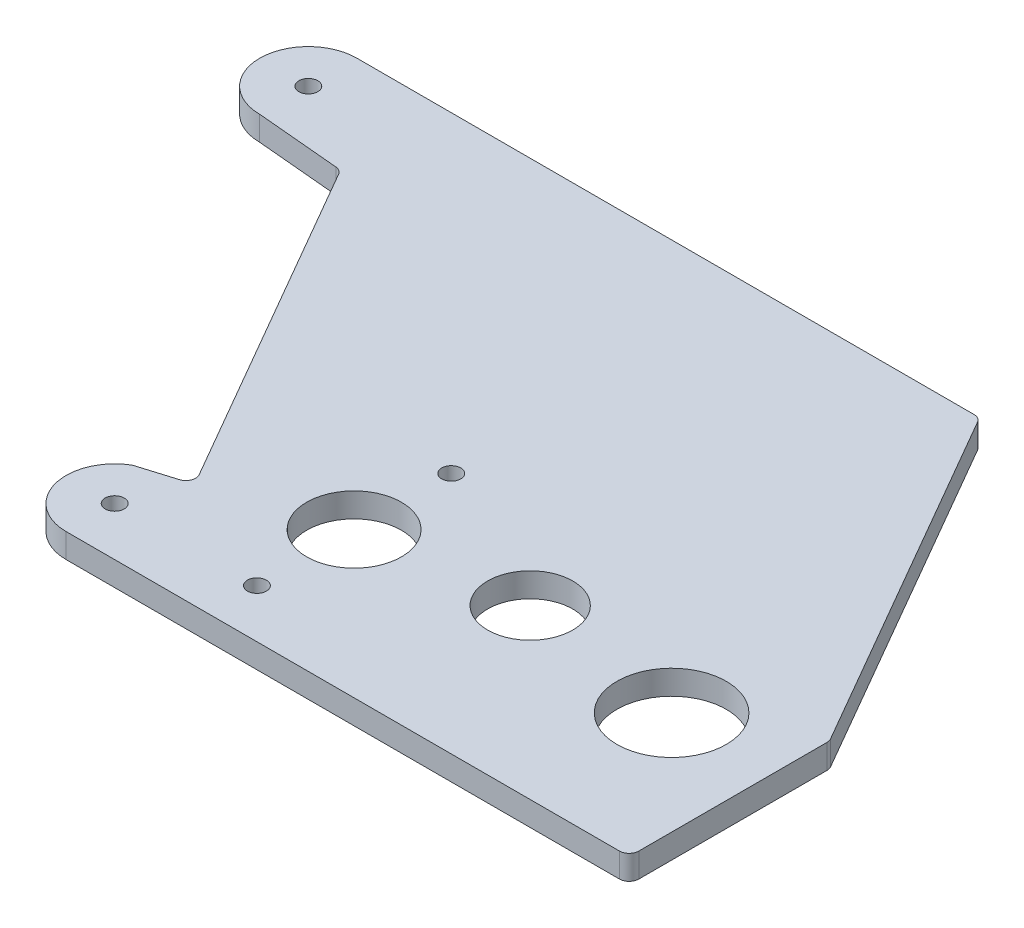
SolidWorks part; units mm, degrees
ref_plane "Front Plane" through (0, 0, 0) normal (0, 0, 1) x (1, 0, 0)
ref_plane "Top Plane" through (0, 0, 0) normal (0, 1, 0) x (1, 0, 0)
ref_plane "Right Plane" through (0, 0, 0) normal (1, 0, 0) x (0, 0, -1)
sketch "Sketch1" plane through (0, 0, 0) normal (0, 1, 0) x (1, 0, 0)
  line L0 (-190.7858, 72.591) -> (-106.965, -72.591)
  line L1 (-190.7858, 72.591) -> (190.7858, 72.591)
  line L2 (-190.7858, 72.591) -> (-190.7858, -72.591)
  line L3 (-190.7858, -72.591) -> (190.7858, -72.591)
  line L4 (190.7858, 72.591) -> (190.7858, -72.591)
  line L5 (-190.7858, 72.591) -> (190.7858, -72.591) construction
  line L6 (-190.7858, -72.591) -> (190.7858, 72.591) construction
  line L7 (-161.4564, 72.591) -> (-77.6356, -72.591)
  line L8 (-176.1211, 72.591) -> (-92.3003, -72.591) construction
  line L9 (-62.4429, -34.491) -> (-22.2218, -28.6714) construction
  line L10 (-22.2218, -28.6714) -> (20.5643, -34.491) construction
  line L11 (20.5643, -34.491) -> (-62.4429, -34.491) construction
  line L12 (47.5645, 72.591) -> (47.5645, -72.591)
  line L13 (-168.7887, 47.191) -> (-145.5814, 45.0947)
  line L14 (-105.9826, -48.8924) -> (-93.5106, -45.0947)
  circle A0 centre (-62.4429, -34.491) radius 32.2072
  circle A1 centre (-62.4429, -34.491) radius 12.3825
  circle A2 centre (-62.4429, -9.091) radius 2.4892
  circle A3 centre (-62.4429, -59.891) radius 2.4892
  circle A4 centre (-22.2218, -28.6714) radius 11.1252
  circle A5 centre (20.5643, -34.491) radius 14.3002
  circle A6 centre (-168.7887, 59.891) radius 2.4892
  circle A7 centre (-99.6326, -59.891) radius 2.4892
  circle A8 centre (-168.7887, 59.891) radius 12.7
  circle A9 centre (-99.6326, -59.891) radius 12.7
  point P0 (0, 0)
  dimension "D2" = 120
  dimension "D5" = 64.4144
  dimension "D6" = 24.765
  dimension "D7" = 4.9784
  dimension "D8" = 4.9784
  dimension "D9" = 50.8
  dimension "D10" = 25.4
  dimension "D11" = 12.7
  dimension "D15" = 22.2504
  dimension "D16" = 28.6004
  dimension "D18" = 4.9784
  dimension "D19" = 4.9784
  dimension "D20" = 12.7
  dimension "D21" = 12.7
  dimension "D22" = 25.4
  dimension "D23" = 31.75
  dimension "D1" = 145.1819
  dimension "D3" = 25.4
  dimension "D4" = 12.7
  dimension "D12" = 40.64
  dimension "D13" = 43.18
  dimension "D14" = 83.0072
  dimension "D17" = 27.0002
  dimension "D24" = 31.75
  dimension "D25" = 125.161
  dimension "D26" = 23.3018
extrude "Boss-Extrude1" add sketch "Sketch1" along normal blind 6.35 contours A4 A0 L7 L3 L12 L1 A5 | A4 A0 A3 A2 A1 | A9 L14 A7 | A9 L7 L14 | A9 L3 L7 | A8 A6 | A8 L13 L7 | A8 L7 L1
sketch "Sketch2" plane through (0, 6.35, 0) normal (0, 1, 0) x (1, 0, 0)
  line L0 (-145.5814, 45.0947) -> (-93.5106, -45.0947)
  line L1 (-154.124, 72.591) -> (-70.3032, -72.591)
  line L2 (-168.7887, 72.591) -> (47.5645, 72.591) construction
  line L3 (-99.6326, -72.591) -> (47.5645, -72.591) construction
  line L4 (-150.4579, 66.241) -> (47.5645, 66.241)
  line L5 (47.5645, 72.591) -> (47.5645, -72.591) construction
  line L6 (41.2145, 72.591) -> (41.2145, -72.591)
  line L7 (-73.9694, -66.241) -> (41.2145, -66.241)
  line L8 (-62.4429, -9.091) -> (-105.9359, 66.241) construction
  line L9 (-22.2218, -28.6714) -> (-22.2218, 66.241) construction
  line L10 (20.5643, -34.491) -> (20.5643, -66.241) construction
  line L11 (-22.2218, -28.6714) -> (1.5143, -59.891) construction
  line L12 (-22.2218, -28.6714) -> (20.5643, -34.491) construction
  line L13 (-139.2615, 46.8482) -> (41.2145, 46.8482) construction
  line L14 (-141.0946, 50.0232) -> (41.2145, 50.0232)
  line L15 (-137.4284, 43.6732) -> (41.2145, 43.6732)
  line L16 (-109.602, 66.241) -> (-72.6391, 2.2194)
  line L17 (-102.2697, 66.241) -> (-66.0124, 3.4415)
  line L18 (-25.3968, 66.241) -> (-25.3968, -11.487)
  line L19 (-19.0468, 66.241) -> (-19.0468, -11.487)
  line L20 (-4.7663, -27.8414) -> (0.7737, -28.5949)
  line L21 (-5.6221, -34.1334) -> (-0.0821, -34.887)
  line L22 (34.8645, 72.591) -> (34.8645, -72.591)
  line L23 (-14.3487, -44.2726) -> (-8.4556, -52.0238)
  line L24 (-9.2938, -40.4294) -> (-3.4006, -48.1806)
  line L25 (-19.0468, 66.241) -> (34.8645, -19.5935)
  line L26 (-27.416, 66.241) -> (22.9704, -13.9814)
  line L27 (-13.2415, 43.6732) -> (22.9704, -13.9814) construction
  line L28 (4.8645, 14.8459) -> (-19.0468, -0.1724) construction
  line L29 (-19.0468, 66.241) -> (-23.0351, 72.591)
  line L30 (-27.416, 66.241) -> (-31.4043, 72.591)
  line L31 (34.8645, -19.5935) -> (47.5645, -39.8137)
  line L32 (2.8001, 13.5493) -> (-22.2218, -28.6714) construction
  line L33 (2.8001, 13.5493) -> (20.5643, -34.491) construction
  line L34 (-4.5097, 7.4426) -> (-16.192, -12.2694)
  line L35 (0.953, 4.2051) -> (-10.7292, -15.5069)
  line L36 (2.9367, 4.0253) -> (10.5095, -16.454)
  line L37 (8.8926, 6.2276) -> (16.4653, -14.2517)
  circle A0 centre (-62.4429, -34.491) radius 38.1
  circle A1 centre (-22.2218, -28.6714) radius 17.4752
  circle A2 centre (20.5643, -34.491) radius 20.6502
  circle A3 centre (1.5143, -59.891) radius 2.1527
  circle A4 centre (1.5143, -59.891) radius 12.7
  circle A5 centre (-94.7395, 46.8482) radius 2.1527
  circle A6 centre (-94.7395, 46.8482) radius 9.525
  circle A7 centre (-22.2218, 46.8482) radius 2.1527
  circle A8 centre (-22.2218, 46.8482) radius 9.525
  circle A9 centre (2.8001, 13.5493) radius 9.525
  circle A10 centre (2.8001, 13.5493) radius 2.1527
  point P68 (-13.2415, 43.6732)
  line M27 (-99.6326, -72.591) -> (47.5645, -72.591)
  line M28 (47.5645, -72.591) -> (47.5645, 72.591)
  line M29 (47.5645, 72.591) -> (-168.7887, 72.591)
  dimension "D5" = 34.9504
  dimension "D6" = 41.3004
  dimension "D7" = 4.3053
  dimension "D9" = 25.4
  dimension "D11" = 4.3053
  dimension "D12" = 19.05
  dimension "D13" = 4.3053
  dimension "D14" = 19.05
  dimension "D21" = 19.05
  dimension "D22" = 4.3053
  dimension "D1" = 6.35
  dimension "D2" = 6.35
  dimension "D3" = 6.35
  dimension "D4" = 6.35
  dimension "D8" = 19.05
  dimension "D10" = 1.7536
  dimension "D15" = 6.35
  dimension "D16" = 6.35
  dimension "D17" = 6.35
  dimension "D18" = 6.35
  dimension "D19" = 12.7
  dimension "D20" = 6.35
  dimension "D23" = 6.35
  dimension "D24" = 6.35
extrude "Cut-Extrude2" [suppressed] cut sketch "Sketch2" against normal through all contours L6 L31 L4 M28 | L6 L4 M29 M28 | L4 L22 L14 L6 | L22 L4 L6 M29 | L29 L4 L22 M29 | L4 L25 L14 L22 | L14 L25 L15 L22 | L14 L22 L15 L6 | L15 L25 L22 | A2 L31 L6 L15 L22 | L31 L6 M27 M28 | A4 L7 L22 A2 | A4 L23 A1 A0 L7 | A9 L35 A1 L20 A2 L36 | A9 L26 A8 L19 A1 L34 | A8 L15 A6 L17 A0 A1 L18 | A8 L18 L26 L4 L17 A6 L14 | A6 L16 L4 L1 L14 | A6 L15 L1 A0 L16 | A5 | A7 | A8 L26 L18 | A10 | A3 | L31 A2
fillet "Fillet1" [suppressed] radius 2.54
sketch "Sketch3" plane through (0, 6.35, 0) normal (0, 1, 0) x (1, 0, 0)
  line L0 (47.5645, -20.1908) -> (-6.0031, 72.591)
  line L1 (47.5645, 72.591) -> (47.5645, -72.591) construction
  line L2 (-168.7887, 72.591) -> (47.5645, 72.591) construction
  line L3 (-6.0031, 72.591) -> (47.5645, 72.591)
  line L4 (47.5645, 72.591) -> (47.5645, -20.1908)
  line L5 (-145.5814, 45.0947) -> (-93.5106, -45.0947) construction
extrude "Cut-Extrude3" cut sketch "Sketch3" against normal through all
fillet "Fillet2" radius 2.54 5 edges at (47.5645, 3.175, 72.591) (47.5645, 3.175, 20.1908) (-6.0031, 3.175, -72.591) (-145.5814, 3.175, -45.0947) (-93.5106, 3.175, 45.0947)
